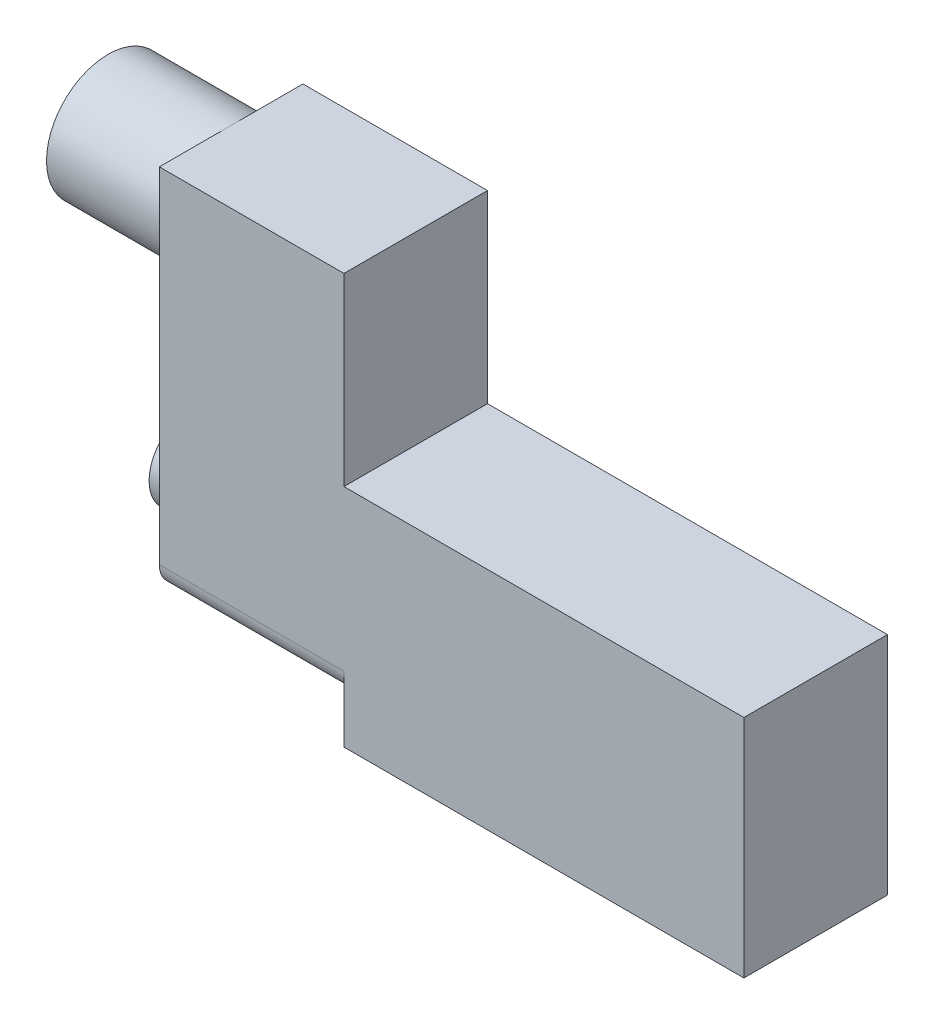
SolidWorks part; units mm, degrees
ref_plane "Front Plane" through (0, 0, 0) normal (0, 0, 1) x (1, 0, 0)
ref_plane "Top Plane" through (0, 0, 0) normal (0, 1, 0) x (1, 0, 0)
ref_plane "Right Plane" through (0, 0, 0) normal (1, 0, 0) x (0, 0, -1)
sketch "Sketch1" plane through (0, 0, 0) normal (0, 1, 0) x (1, 0, 0)
  line L1 (0, 0) -> (61.9125, 0)
  line L2 (0, 0) -> (0, 22.225)
  line L3 (0, 22.225) -> (61.9125, 22.225)
  line L4 (61.9125, 0) -> (61.9125, 22.225)
  dimension "D1" = 61.9125
  dimension "D2" = 22.225
extrude "Boss-Extrude1" add sketch "Sketch1" along normal blind 34.925
sketch "Sketch2" plane through (0, 0, 0) normal (-1, 0, 0) x (0, 0, 1)
  line L0 (0, 34.925) -> (0, 0) construction
  line L1 (-22.225, 34.925) -> (0, 34.925)
  line L2 (-22.225, 34.925) -> (-22.225, 6.35)
  line L3 (-22.225, 6.35) -> (0, 6.35)
  line L4 (0, 34.925) -> (0, 6.35)
  dimension "D1" = 28.575
extrude "Boss-Extrude2" add sketch "Sketch2" along normal blind 28.575
sketch "Sketch3" plane through (0, 34.925, 0) normal (0, 1, 0) x (1, 0, 0)
  line L0 (-28.575, 0) -> (61.9125, 0) construction
  line L1 (-28.575, 22.225) -> (0, 22.225)
  line L2 (-28.575, 22.225) -> (-28.575, 0)
  line L3 (-28.575, 0) -> (0, 0)
  line L4 (0, 22.225) -> (0, 0)
  dimension "D1" = 28.575
extrude "Boss-Extrude3" add sketch "Sketch3" along normal blind 28.575
sketch "Sketch5" plane through (-28.575, 0, 0) normal (-1, 0, 0) x (0, 0, 1)
  line L0 (-11.1125, 63.5) -> (-11.1125, 6.35) construction
  line L1 (-22.225, 63.5) -> (0, 63.5) construction
  line L2 (-22.225, 6.35) -> (0, 6.35) construction
  circle A0 centre (-11.1125, 15.875) radius 6.35
  dimension "D1" = 12.7
  dimension "D2" = 9.525
extrude "Boss-Extrude5" add sketch "Sketch5" along normal blind 6.35
fillet "Fillet1" radius 3.81 2 edges
sketch "Sketch6" plane through (-28.575, 0, 0) normal (-1, 0, 0) x (0, 0, 1)
  line L0 (-22.225, 63.5) -> (0, 63.5) construction
  line L3 (-11.1125, 63.5) -> (-11.1125, 31.7909) construction
  circle A0 centre (-11.1125, 53.975) radius 9.525
  point P4 (-11.1125, 63.5)
  dimension "D1" = 19.05
extrude "Boss-Extrude6" add sketch "Sketch6" along normal blind 19.05
